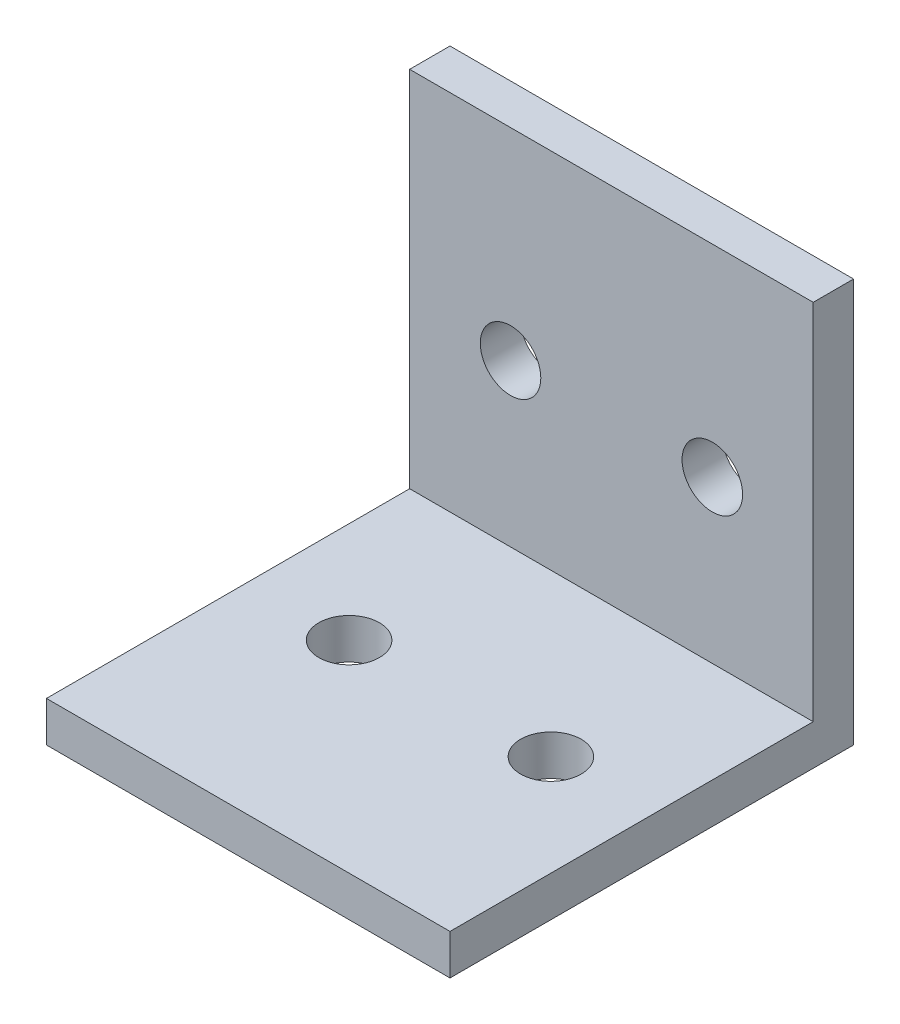
SolidWorks part; units mm, degrees
ref_plane "前视基准面" through (0, 0, 0) normal (0, 0, 1) x (1, 0, 0)
ref_plane "上视基准面" through (0, 0, 0) normal (0, 1, 0) x (1, 0, 0)
ref_plane "右视基准面" through (0, 0, 0) normal (1, 0, 0) x (0, 0, -1)
sketch "草图1" plane through (0, 0, 0) normal (0, 0, 1) x (1, 0, 0)
  line L1 (-10, 10) -> (10, 10)
  line L2 (-10, 10) -> (-10, -10)
  line L3 (-10, -10) -> (10, -10)
  line L4 (10, 10) -> (10, -10)
  line L5 (-10, 10) -> (10, -10) construction
  line L6 (-10, -10) -> (10, 10) construction
  point P0 (0, 0)
  dimension "D1" = 20
  dimension "D2" = 20
extrude "凸台-拉伸1" add sketch "草图1" along normal blind 2
sketch "草图2" plane through (0, 0, 2) normal (0, 0, 1) x (1, 0, 0)
  line L0 (10, -10) -> (10, 10) construction
  line L1 (-10, -10) -> (10, -10)
  line L2 (-10, -10) -> (-10, -8)
  line L3 (-10, -8) -> (10, -8)
  line L4 (10, -10) -> (10, -8)
  dimension "D1" = 2
extrude "凸台-拉伸2" add sketch "草图2" along normal blind 18
sketch "草图4" plane through (0, -10, 0) normal (0, -1, 0) x (1, 0, 0)
  line L0 (-10, 20) -> (-10, 0) construction
  line L1 (10, 20) -> (10, 0) construction
  line L2 (-10, 20) -> (10, 20) construction
  circle A0 centre (-5, 10) radius 1.5
  circle A1 centre (5, 10) radius 1.5
  point P10 (0, 0)
  dimension "D1" = 3
  dimension "D2" = 3
  dimension "D3" = 5
  dimension "D4" = 5
  dimension "D5" = 10
extrude "切除-拉伸1" cut sketch "草图4" against normal blind 18
sketch "草图5" plane through (0, 0, 0) normal (0, 0, -1) x (-1, 0, 0)
sketch "草图6" plane through (0, 0, 0) normal (0, 0, -1) x (-1, 0, 0)
  line L0 (-10, -10) -> (-10, 10) construction
  line L1 (10, 10) -> (10, -10) construction
  line L2 (10, -10) -> (-10, -10) construction
  circle A0 centre (5, 0) radius 1.5
  circle A1 centre (-5, 0) radius 1.5
  point P10 (0, 0)
  dimension "D1" = 3
  dimension "D2" = 3
  dimension "D3" = 5
  dimension "D4" = 5
  dimension "D5" = 10
extrude "切除-拉伸2" cut sketch "草图6" against normal blind 18
